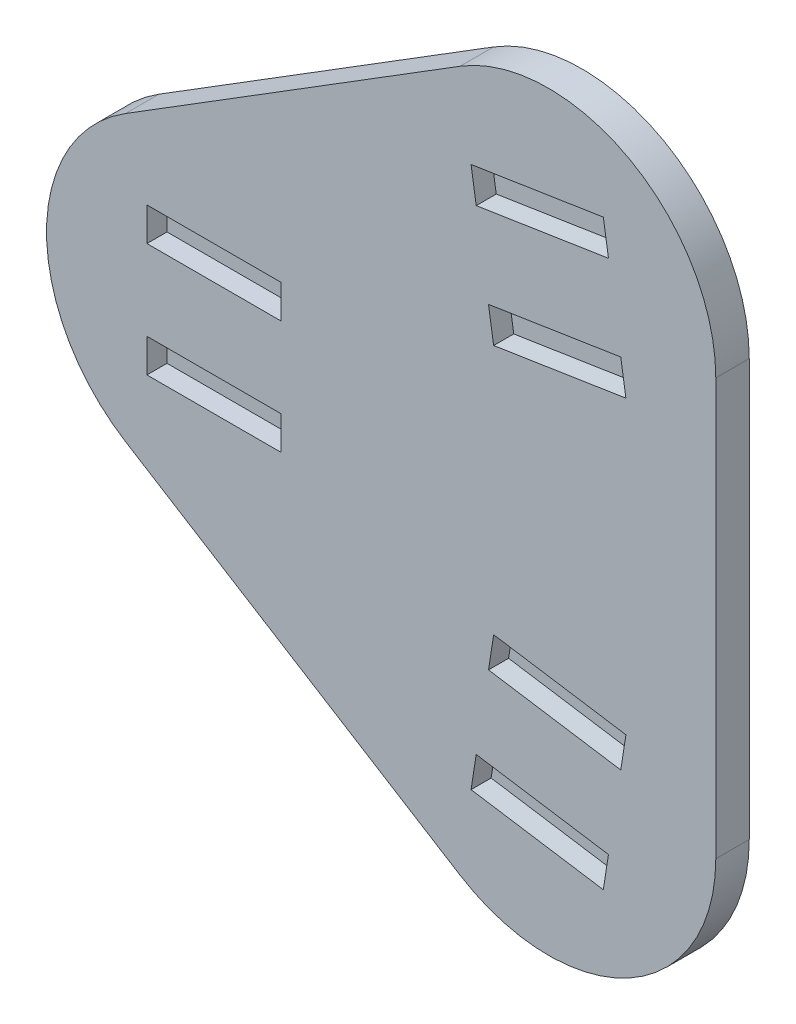
SolidWorks part; units mm, degrees
ref_plane "Ön Düzlem" through (0, 0, 0) normal (0, 0, 1) x (1, 0, 0)
ref_plane "Üst Düzlem" through (0, 0, 0) normal (0, 1, 0) x (1, 0, 0)
ref_plane "Sağ Düzlem" through (0, 0, 0) normal (1, 0, 0) x (0, 0, -1)
sketch "Çizim1" plane through (0, 0, 0) normal (0, 0, 1) x (1, 0, 0)
  line L0 (6.1975, -35.5087) -> (5.43, -40.4495)
  line L1 (5.43, -40.4495) -> (25.193, -43.5194)
  line L2 (25.193, -43.5194) -> (25.9605, -38.5787)
  line L3 (25.9605, -38.5787) -> (16.079, -37.0437)
  line L4 (16.079, -37.0437) -> (6.1975, -35.5087)
  line L5 (8.807, -18.7102) -> (8.0395, -23.6509)
  line L6 (8.0395, -23.6509) -> (17.921, -25.1859)
  line L7 (17.921, -25.1859) -> (27.8025, -26.7209)
  line L8 (27.8025, -26.7209) -> (28.57, -21.7802)
  line L9 (28.57, -21.7802) -> (8.807, -18.7102)
  line L10 (-23, -11) -> (-23, -6)
  line L11 (-43, -6) -> (-43, -11)
  line L12 (-23, 6) -> (-23, 11)
  line L13 (-43, 11) -> (-43, 6)
  line L14 (17.921, 25.1859) -> (8.0395, 23.6509)
  line L15 (8.0395, 23.6509) -> (8.807, 18.7102)
  line L16 (8.807, 18.7102) -> (28.57, 21.7802)
  line L17 (28.57, 21.7802) -> (27.8025, 26.7209)
  line L18 (27.8025, 26.7209) -> (17.921, 25.1859)
  line L19 (16.079, 37.0437) -> (25.9605, 38.5787)
  line L20 (25.9605, 38.5787) -> (25.193, 43.5194)
  line L21 (25.193, 43.5194) -> (5.43, 40.4495)
  line L22 (5.43, 40.4495) -> (6.1975, 35.5087)
  line L23 (6.1975, 35.5087) -> (16.079, 37.0437)
  line L24 (-43, 11) -> (-23, 11)
  line L25 (-43, 6) -> (-23, 6)
  line L26 (-43, -6) -> (-23, -6)
  line L27 (-43, -11) -> (-23, -11)
  circle A0 centre (0, 0) radius 65
extrude "Yükseklik-Ekstrüzyon1" add sketch "Çizim1" along normal blind 3
sketch "Çizim2" plane through (0, 0, 0) normal (0, 0, -1) x (-1, 0, 0)
  circle A1 centre (0, 0) radius 65
  circle A2 centre (0, 0) radius 65
  dimension "D1" = 0
extrude "Yükseklik-Ekstrüzyon2" add sketch "Çizim2" along normal blind 2
sketch "Sketch1" plane through (0, 0, 3) normal (0, 0, 1) x (1, 0, 0)
  line L0 (-43, -11) -> (-23, 11) construction
  line L1 (5.43, -40.4495) -> (28.57, -21.7802) construction
  line L2 (5.43, 40.4495) -> (28.57, 21.7802) construction
  line L3 (-46.2087, -21.2257) -> (3.7913, -52.3405)
  line L4 (-46.2087, 21.2257) -> (3.7913, 52.3405)
  line L5 (42, -31.1148) -> (42, 31.1148)
  arc A1 (-46.2087, 21.2257) -> (-46.2087, -21.2257) centre (-33, 0) ccw
  arc A2 (42, 31.1148) -> (3.7913, 52.3405) centre (17, 31.1148) ccw
  arc A3 (3.7913, -52.3405) -> (42, -31.1148) centre (17, -31.1148) ccw
  circle A4 centre (0, 0) radius 5 construction
  point P22 (37, 71.6839)
  dimension "D1" = 50
  dimension "D2" = 50
  dimension "D3" = 50
  dimension "D4" = 10
extrude "Cut-Extrude1" cut sketch "Sketch1" against normal blind 10 flip side to cut
